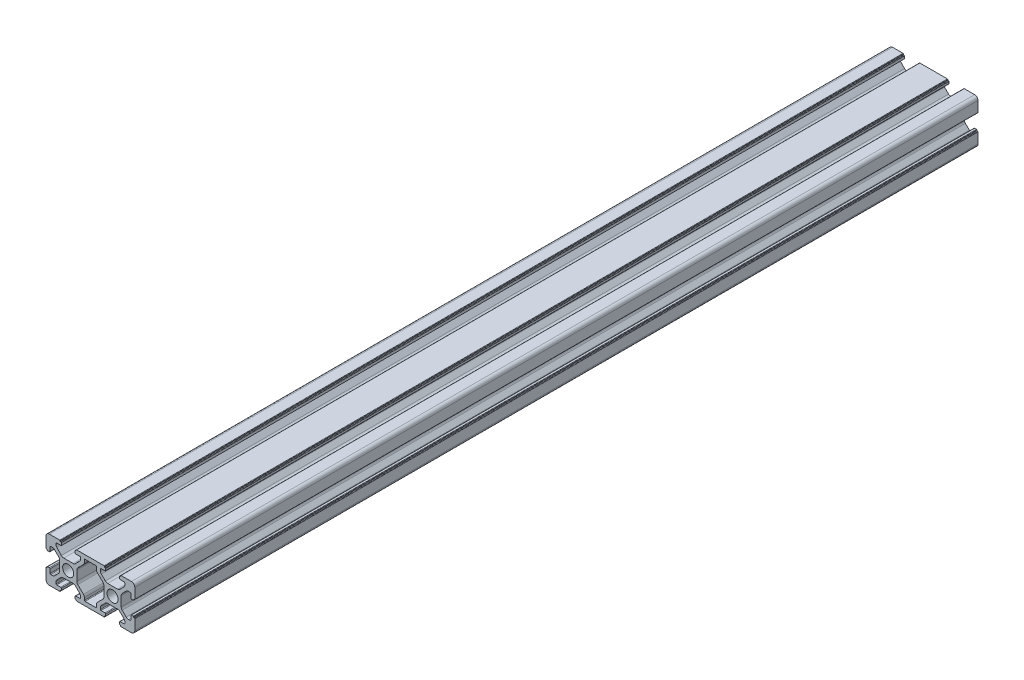
SolidWorks part; units mm, degrees
material "6063-T5"
ref_plane "Front Plane" through (0, 0, 0) normal (0, 0, 1) x (1, 0, 0)
ref_plane "Top Plane" through (0, 0, 0) normal (0, 1, 0) x (1, 0, 0)
ref_plane "Right Plane" through (0, 0, 0) normal (1, 0, 0) x (0, 0, -1)
sketch "Sketch1" plane through (0, 0, 0) normal (0, 0, 1) x (1, 0, 0)
  line L0 (1.5, 0) -> (6.2, 0)
  line L1 (40, 1.5) -> (40, 6.2)
  line L2 (38.5, 20) -> (33.8, 20)
  line L3 (0, 18.5) -> (0, 13.8)
  line L4 (17.6, 1.8) -> (22.4, 1.8)
  line L5 (32.218, 13.9) -> (27.782, 13.9)
  line L6 (26.1, 12.218) -> (26.1, 7.782)
  line L7 (17.6, 18.2) -> (22.4, 18.2)
  line L8 (12.218, 13.9) -> (7.9864, 13.9)
  line L9 (6.1, 12.218) -> (6.1, 7.782)
  line L10 (7.782, 6.1) -> (12.218, 6.1)
  line L11 (13.9, 7.782) -> (13.9, 12.218)
  line L12 (27.782, 6.1) -> (32.218, 6.1)
  line L13 (33.9, 7.782) -> (33.9, 12.218)
  line L14 (26.7213, 14.3393) -> (24.9393, 16.1213)
  line L15 (33.2787, 14.3393) -> (35.0607, 16.1213)
  line L16 (34.3393, 13.2787) -> (36.1213, 15.0607)
  line L17 (25.6607, 6.7213) -> (23.1393, 4.2)
  line L18 (15.2, 1.8) -> (13.4, 1.8)
  line L19 (26.7213, 5.6607) -> (24.9393, 3.8787)
  line L20 (24.8, 1.8) -> (26.6, 1.8)
  line L21 (15.3, 18.2) -> (13.1, 18.2)
  line L22 (13.2787, 14.3393) -> (15.1607, 16.2213)
  line L23 (14.3393, 13.2787) -> (16.8607, 15.8)
  line L24 (5.6607, 6.7213) -> (3.8787, 4.9393)
  line L25 (6.7213, 5.6607) -> (4.9393, 3.8787)
  line L26 (6.897, 14.3689) -> (4.9106, 16.4674)
  line L27 (5.6607, 13.2787) -> (3.8787, 15.0607)
  line L28 (14.3393, 6.7213) -> (16.8607, 4.2)
  line L29 (13.2787, 5.6607) -> (15.0607, 3.8787)
  line L30 (24.8, 18.2) -> (26.6, 18.2)
  line L31 (25.6607, 13.2787) -> (23.1393, 15.8)
  line L32 (34.3393, 6.7213) -> (36.1213, 4.9393)
  line L33 (33.2787, 5.6607) -> (35.0607, 3.8787)
  line L34 (1.8, 15.2) -> (1.8, 13.4)
  line L35 (24.5, 2.1) -> (24.5, 2.818)
  line L36 (4.5, 2.1) -> (4.5, 2.818)
  line L37 (2.818, 4.5) -> (2.1, 4.5)
  line L38 (4.5, 17.9) -> (4.5, 17.4986)
  line L39 (2.818, 15.5) -> (2.1, 15.5)
  line L40 (15.6, 17.9) -> (15.6, 17.282)
  line L41 (15.5, 2.818) -> (15.5, 2.1)
  line L42 (38.2, 15.2) -> (38.2, 13.4)
  line L43 (35.5, 2.818) -> (35.5, 2.1)
  line L44 (37.182, 4.5) -> (37.9, 4.5)
  line L45 (35.5, 17.182) -> (35.5, 17.9)
  line L46 (37.182, 15.5) -> (37.9, 15.5)
  line L47 (17.3, 2.1) -> (17.3, 3.1393)
  line L48 (22.7, 2.1) -> (22.7, 3.1393)
  line L49 (17.3, 17.9) -> (17.3, 16.8607)
  line L50 (22.7, 17.9) -> (22.7, 16.8607)
  line L51 (24.5, 17.9) -> (24.5, 17.182)
  line L52 (6.9, 19.3) -> (6.9, 18.2)
  line L53 (13.1, 19.3) -> (13.1, 18.2)
  line L54 (6.9, 1.5) -> (6.9, 0.7)
  line L55 (13.1, 1.5) -> (13.1, 0.7)
  line L56 (13.8, 0) -> (26.2, 0)
  line L57 (6.6, 1.8) -> (4.8, 1.8)
  line L58 (6.9, 18.2) -> (4.8, 18.2)
  line L59 (6.2, 20) -> (1.5, 20)
  line L60 (39.3, 6.9) -> (38.5, 6.9)
  line L61 (39.3, 13.1) -> (38.5, 13.1)
  line L62 (1.5, 13.1) -> (0.7, 13.1)
  line L63 (1.5, 6.9) -> (0.7, 6.9)
  line L64 (0, 6.2) -> (0, 1.5)
  line L65 (1.8, 6.6) -> (1.8, 4.8)
  line L66 (38.2, 6.6) -> (38.2, 4.8)
  line L67 (40, 13.8) -> (40, 18.5)
  line L68 (33.1, 19.3) -> (33.1, 18.5)
  line L69 (26.9, 19.3) -> (26.9, 18.5)
  line L70 (26.9, 1.5) -> (26.9, 0.7)
  line L71 (33.1, 1.5) -> (33.1, 0.7)
  line L72 (33.8, 0) -> (38.5, 0)
  line L73 (33.4, 1.8) -> (35.2, 1.8)
  line L74 (26.2, 20) -> (13.8, 20)
  line L75 (33.4, 18.2) -> (35.2, 18.2)
  line L76 (6.7, 0.5) -> (6.6, 0.5)
  line L77 (6.4, 0.3) -> (6.4, 0.2)
  line L78 (13.3, 0.5) -> (13.4, 0.5)
  line L79 (13.6, 0.3) -> (13.6, 0.2)
  line L80 (26.7, 0.5) -> (26.6, 0.5)
  line L81 (26.4, 0.3) -> (26.4, 0.2)
  line L82 (33.3, 0.5) -> (33.4, 0.5)
  line L83 (33.6, 0.3) -> (33.6, 0.2)
  line L85 (6.4, 19.8) -> (6.4, 19.7)
  line L86 (6.6, 19.5) -> (6.7, 19.5)
  line L87 (13.6, 19.8) -> (13.6, 19.7)
  line L88 (13.4, 19.5) -> (13.3, 19.5)
  line L89 (26.4, 19.8) -> (26.4, 19.7)
  line L90 (26.6, 19.5) -> (26.7, 19.5)
  line L91 (33.6, 19.8) -> (33.6, 19.7)
  line L92 (33.4, 19.5) -> (33.3, 19.5)
  line L93 (0.5, 13.3) -> (0.5, 13.4)
  line L94 (0.3, 13.6) -> (0.2, 13.6)
  line L95 (0.5, 6.7) -> (0.5, 6.6)
  line L96 (0.3, 6.4) -> (0.2, 6.4)
  line L97 (39.5, 13.3) -> (39.5, 13.4)
  line L98 (39.7, 13.6) -> (39.8, 13.6)
  line L99 (39.5, 6.7) -> (39.5, 6.6)
  line L100 (39.7, 6.4) -> (39.8, 6.4)
  circle A0 centre (10, 10) radius 2.5
  circle A1 centre (30, 10) radius 2.5
  arc A2 (38.5, 0) -> (40, 1.5) centre (38.5, 1.5) ccw
  arc A3 (40, 18.5) -> (38.5, 20) centre (38.5, 18.5) ccw
  arc A4 (1.5, 0) -> (0, 1.5) centre (1.5, 1.5) cw
  arc A5 (1.5, 20) -> (0, 18.5) centre (1.5, 18.5) ccw
  arc A6 (26.7213, 5.6607) -> (27.782, 6.1) centre (27.782, 4.6) cw
  arc A7 (32.218, 6.1) -> (33.2787, 5.6607) centre (32.218, 4.6) cw
  arc A8 (33.9, 7.782) -> (34.3393, 6.7213) centre (35.4, 7.782) ccw
  arc A9 (33.2787, 14.3393) -> (32.218, 13.9) centre (32.218, 15.4) cw
  arc A10 (14.3393, 6.7213) -> (13.9, 7.782) centre (15.4, 7.782) cw
  arc A11 (14.3393, 13.2787) -> (13.9, 12.218) centre (15.4, 12.218) ccw
  arc A12 (25.6607, 6.7213) -> (26.1, 7.782) centre (24.6, 7.782) ccw
  arc A13 (26.1, 12.218) -> (25.6607, 13.2787) centre (24.6, 12.218) ccw
  arc A14 (27.782, 13.9) -> (26.7213, 14.3393) centre (27.782, 15.4) cw
  arc A15 (5.6607, 13.2787) -> (6.1, 12.218) centre (4.6, 12.218) cw
  arc A16 (5.6607, 6.7213) -> (6.1, 7.782) centre (4.6, 7.782) ccw
  arc A17 (13.2787, 5.6607) -> (12.218, 6.1) centre (12.218, 4.6) ccw
  arc A18 (6.7213, 5.6607) -> (7.782, 6.1) centre (7.782, 4.6) cw
  arc A19 (13.2787, 14.3393) -> (12.218, 13.9) centre (12.218, 15.4) cw
  arc A20 (6.897, 14.3689) -> (7.9864, 13.9) centre (7.9864, 15.4) ccw
  arc A21 (36.1213, 4.9393) -> (37.182, 4.5) centre (37.182, 6) ccw
  arc A22 (36.1213, 15.0607) -> (37.182, 15.5) centre (37.182, 14) cw
  arc A23 (35.0607, 16.1213) -> (35.5, 17.182) centre (34, 17.182) ccw
  arc A24 (24.5, 17.182) -> (24.9393, 16.1213) centre (26, 17.182) ccw
  arc A25 (22.7, 16.8607) -> (23.1393, 15.8) centre (24.2, 16.8607) ccw
  arc A26 (17.3, 16.8607) -> (16.8607, 15.8) centre (15.8, 16.8607) cw
  arc A27 (4.9106, 16.4674) -> (4.5, 17.4986) centre (6, 17.4986) cw
  arc A28 (15.6, 17.282) -> (15.1607, 16.2213) centre (14.1, 17.282) cw
  arc A29 (3.8787, 15.0607) -> (2.818, 15.5) centre (2.818, 14) ccw
  arc A30 (3.8787, 4.9393) -> (2.818, 4.5) centre (2.818, 6) cw
  arc A31 (4.9393, 3.8787) -> (4.5, 2.818) centre (6, 2.818) ccw
  arc A32 (35.0607, 3.8787) -> (35.5, 2.818) centre (34, 2.818) cw
  arc A33 (24.9393, 3.8787) -> (24.5, 2.818) centre (26, 2.818) ccw
  arc A34 (22.7, 3.1393) -> (23.1393, 4.2) centre (24.2, 3.1393) cw
  arc A35 (17.3, 3.1393) -> (16.8607, 4.2) centre (15.8, 3.1393) ccw
  arc A36 (15.5, 2.818) -> (15.0607, 3.8787) centre (14, 2.818) ccw
  arc A37 (1.8, 6.6) -> (1.5, 6.9) centre (1.5, 6.6) ccw
  arc A38 (1.8, 13.4) -> (1.5, 13.1) centre (1.5, 13.4) cw
  arc A39 (17.6, 18.2) -> (17.3, 17.9) centre (17.6, 17.9) ccw
  arc A40 (22.4, 1.8) -> (22.7, 2.1) centre (22.4, 2.1) ccw
  arc A41 (17.6, 1.8) -> (17.3, 2.1) centre (17.6, 2.1) cw
  arc A42 (15.2, 1.8) -> (15.5, 2.1) centre (15.2, 2.1) ccw
  arc A43 (6.6, 1.8) -> (6.9, 1.5) centre (6.6, 1.5) cw
  arc A44 (13.4, 1.8) -> (13.1, 1.5) centre (13.4, 1.5) ccw
  arc A45 (24.8, 1.8) -> (24.5, 2.1) centre (24.8, 2.1) cw
  arc A46 (35.2, 1.8) -> (35.5, 2.1) centre (35.2, 2.1) ccw
  arc A47 (26.6, 1.8) -> (26.9, 1.5) centre (26.6, 1.5) cw
  arc A48 (33.4, 1.8) -> (33.1, 1.5) centre (33.4, 1.5) ccw
  arc A49 (26.9, 18.5) -> (26.6, 18.2) centre (26.6, 18.5) cw
  arc A50 (33.1, 18.5) -> (33.4, 18.2) centre (33.4, 18.5) ccw
  arc A51 (37.9, 4.5) -> (38.2, 4.8) centre (37.9, 4.8) ccw
  arc A52 (38.5, 13.1) -> (38.2, 13.4) centre (38.5, 13.4) cw
  arc A53 (38.5, 6.9) -> (38.2, 6.6) centre (38.5, 6.6) ccw
  arc A54 (38.2, 15.2) -> (37.9, 15.5) centre (37.9, 15.2) ccw
  arc A55 (35.2, 18.2) -> (35.5, 17.9) centre (35.2, 17.9) cw
  arc A56 (24.8, 18.2) -> (24.5, 17.9) centre (24.8, 17.9) ccw
  arc A57 (22.4, 18.2) -> (22.7, 17.9) centre (22.4, 17.9) cw
  arc A58 (15.3, 18.2) -> (15.6, 17.9) centre (15.3, 17.9) cw
  arc A59 (4.5, 17.9) -> (4.8, 18.2) centre (4.8, 17.9) cw
  arc A60 (1.8, 15.2) -> (2.1, 15.5) centre (2.1, 15.2) cw
  arc A61 (1.8, 4.8) -> (2.1, 4.5) centre (2.1, 4.8) ccw
  arc A62 (4.5, 2.1) -> (4.8, 1.8) centre (4.8, 2.1) ccw
  arc A63 (34.3393, 13.2787) -> (33.9, 12.218) centre (35.4, 12.218) ccw
  arc A64 (6.4, 0.2) -> (6.2, 0) centre (6.2, 0.2) cw
  arc A65 (6.6, 0.5) -> (6.4, 0.3) centre (6.6, 0.3) ccw
  arc A66 (6.7, 0.5) -> (6.9, 0.7) centre (6.7, 0.7) ccw
  arc A67 (13.6, 0.2) -> (13.8, 0) centre (13.8, 0.2) ccw
  arc A68 (13.4, 0.5) -> (13.6, 0.3) centre (13.4, 0.3) cw
  arc A69 (13.3, 0.5) -> (13.1, 0.7) centre (13.3, 0.7) cw
  arc A70 (26.4, 0.2) -> (26.2, 0) centre (26.2, 0.2) cw
  arc A71 (26.6, 0.5) -> (26.4, 0.3) centre (26.6, 0.3) ccw
  arc A72 (26.7, 0.5) -> (26.9, 0.7) centre (26.7, 0.7) ccw
  arc A73 (33.6, 0.2) -> (33.8, 0) centre (33.8, 0.2) ccw
  arc A74 (33.4, 0.5) -> (33.6, 0.3) centre (33.4, 0.3) cw
  arc A75 (33.3, 0.5) -> (33.1, 0.7) centre (33.3, 0.7) cw
  arc A76 (39.8, 6.4) -> (40, 6.2) centre (39.8, 6.2) cw
  arc A77 (39.5, 6.6) -> (39.7, 6.4) centre (39.7, 6.6) ccw
  arc A78 (39.5, 6.7) -> (39.3, 6.9) centre (39.3, 6.7) ccw
  arc A79 (39.5, 13.3) -> (39.3, 13.1) centre (39.3, 13.3) cw
  arc A80 (39.5, 13.4) -> (39.7, 13.6) centre (39.7, 13.4) cw
  arc A81 (39.8, 13.6) -> (40, 13.8) centre (39.8, 13.8) ccw
  arc A82 (33.3, 19.5) -> (33.1, 19.3) centre (33.3, 19.3) ccw
  arc A83 (33.6, 19.7) -> (33.4, 19.5) centre (33.4, 19.7) cw
  arc A84 (33.6, 19.8) -> (33.8, 20) centre (33.8, 19.8) cw
  arc A85 (26.7, 19.5) -> (26.9, 19.3) centre (26.7, 19.3) cw
  arc A86 (26.4, 19.7) -> (26.6, 19.5) centre (26.6, 19.7) ccw
  arc A87 (26.4, 19.8) -> (26.2, 20) centre (26.2, 19.8) ccw
  arc A88 (0.2, 6.4) -> (0, 6.2) centre (0.2, 6.2) ccw
  arc A89 (0.5, 6.6) -> (0.3, 6.4) centre (0.3, 6.6) cw
  arc A90 (0.5, 6.7) -> (0.7, 6.9) centre (0.7, 6.7) cw
  arc A91 (13.3, 19.5) -> (13.1, 19.3) centre (13.3, 19.3) ccw
  arc A92 (13.6, 19.7) -> (13.4, 19.5) centre (13.4, 19.7) cw
  arc A93 (13.6, 19.8) -> (13.8, 20) centre (13.8, 19.8) cw
  arc A94 (6.2, 20) -> (6.4, 19.8) centre (6.2, 19.8) cw
  arc A95 (6.7, 19.5) -> (6.9, 19.3) centre (6.7, 19.3) cw
  arc A96 (6.4, 19.7) -> (6.6, 19.5) centre (6.6, 19.7) ccw
  arc A97 (0.5, 13.3) -> (0.7, 13.1) centre (0.7, 13.3) ccw
  arc A98 (0.2, 13.6) -> (0, 13.8) centre (0.2, 13.8) cw
  arc A99 (0.5, 13.4) -> (0.3, 13.6) centre (0.3, 13.4) ccw
  point P87 (0, 0)
  point P178 (1.8, 6.9)
  point P181 (1.8, 13.1)
  point P186 (22.7, 1.8)
  point P193 (6.9, 1.8)
  point P204 (33.1, 1.8)
  point P209 (33.1, 18.2)
  point P216 (38.2, 6.9)
  point P243 (6.9, 0.5)
  point P248 (13.6, 0.5)
  point P257 (26.9, 0.5)
extrude "Boss-Extrude2" add sketch "Sketch1" along normal blind 380 contours A57 L7 A39 L49 A26 L23 A11 L11 A10 L28 A35 L47 A41 L4 A40 L48 A34 L17 A12 L6 A13 L31 A25 L50 | A0 | A1 | L59 A5 L3 A98 L94 A99 L93 A97 L62 A38 L34 A60 L39 A29 L27 A15 L9 A16 L24 A30 L37 A61 L65 A37 L63 A90 L95 A89 L96 A88 L64 A4 L0 A64 L77 A65 L76 A66 L54 A43 L57 A62 L36 A31 L25 A18 L10 A17 L29 A36 L41 A42 L18 A44 L55 A69 L78 A68 L79 A67 L56 A70 L81 A71 L80 A72 L70 A47 L20 A45 L35 A33 L19 A6 L12 A7 L33 A32 L43 A46 L73 A48 L71 A75 L82 A74 L83 A73 L72 A2 L1 A76 L100 A77 L99 A78 L60 A53 L66 A51 L44 A21 L32 A8 L13 A63 L16 A22 L46 A54 L42 A52 L61 A79 L97 A80 L98 A81 L67 A3 L2 A84 L91 A83 L92 A82 L68 A50 L75 A55 L45 A23 L15 A9 L5 A14 L14 A24 L51 A56 L30 A49 L69 A85 L90 A86 L89 A87 L74 A93 L87 A92 L88 A91 L53 L21 A58 L40 A28 L22 A19 L8 A20 L26 A27 L38 A59 L58 L52 A95 L86 A96 L85 A94
